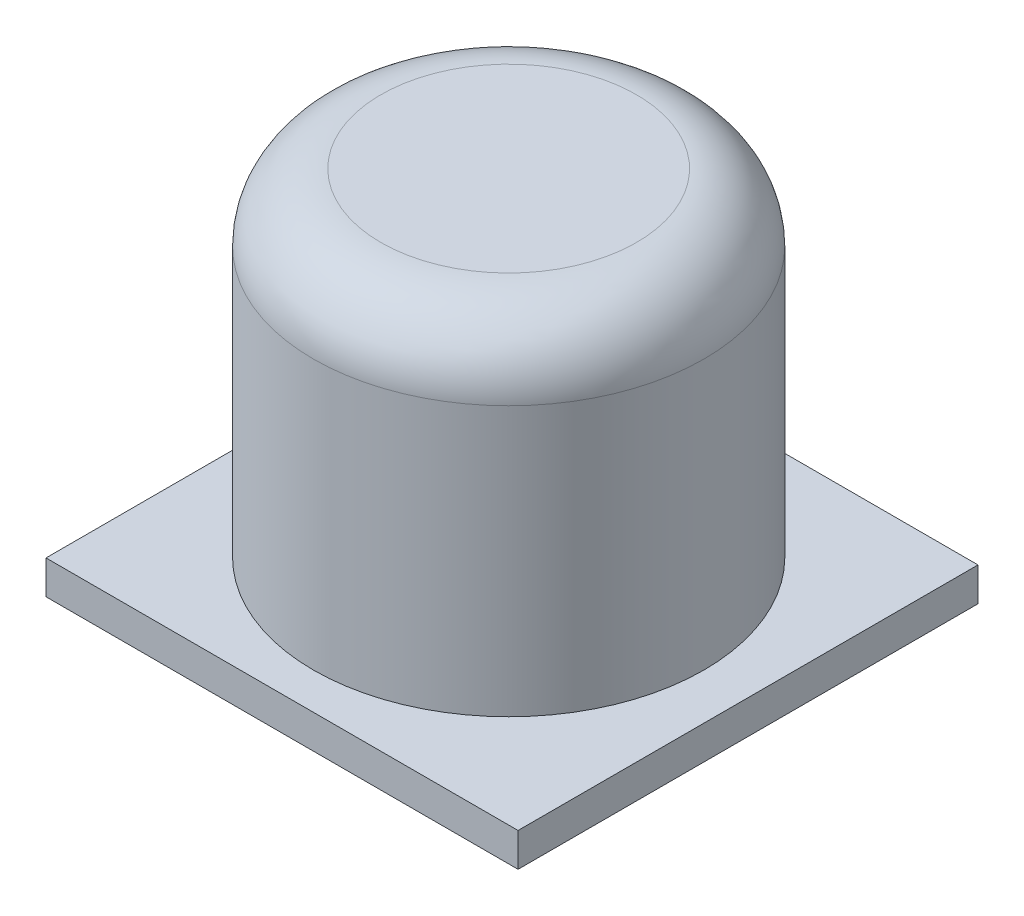
SolidWorks part; units mm, degrees
ref_plane "Front Plane" through (0, 0, 0) normal (0, 0, 1) x (1, 0, 0)
ref_plane "Top Plane" through (0, 0, 0) normal (0, 1, 0) x (1, 0, 0)
ref_plane "Right Plane" through (0, 0, 0) normal (1, 0, 0) x (0, 0, -1)
sketch "Sketch2" plane through (0, 0, 0) normal (0, 1, 0) x (1, 0, 0)
  circle A0 centre (0, 0) radius 2.9
extrude "Boss-Extrude1" add sketch "Sketch2" against normal blind 0.5
sketch "Sketch3" plane through (0, 0, 0) normal (0, 1, 0) x (1, 0, 0)
  circle A0 centre (0, 0) radius 2.9
extrude "Boss-Extrude2" add sketch "Sketch3" along normal blind 5
sketch "Sketch4" plane through (0, 0, 0) normal (0, 1, 0) x (1, 0, 0)
  line L1 (-3.4283, 3.3878) -> (3.5826, 3.3878)
  line L2 (-3.4283, 3.3878) -> (-3.4283, -3.4433)
  line L3 (-3.4283, -3.4433) -> (3.5826, -3.4433)
  line L4 (3.5826, 3.3878) -> (3.5826, -3.4433)
extrude "Boss-Extrude3" add sketch "Sketch4" against normal blind 0.5
fillet "Fillet1" radius 1 1 edges at (0, 5, 2.9)
